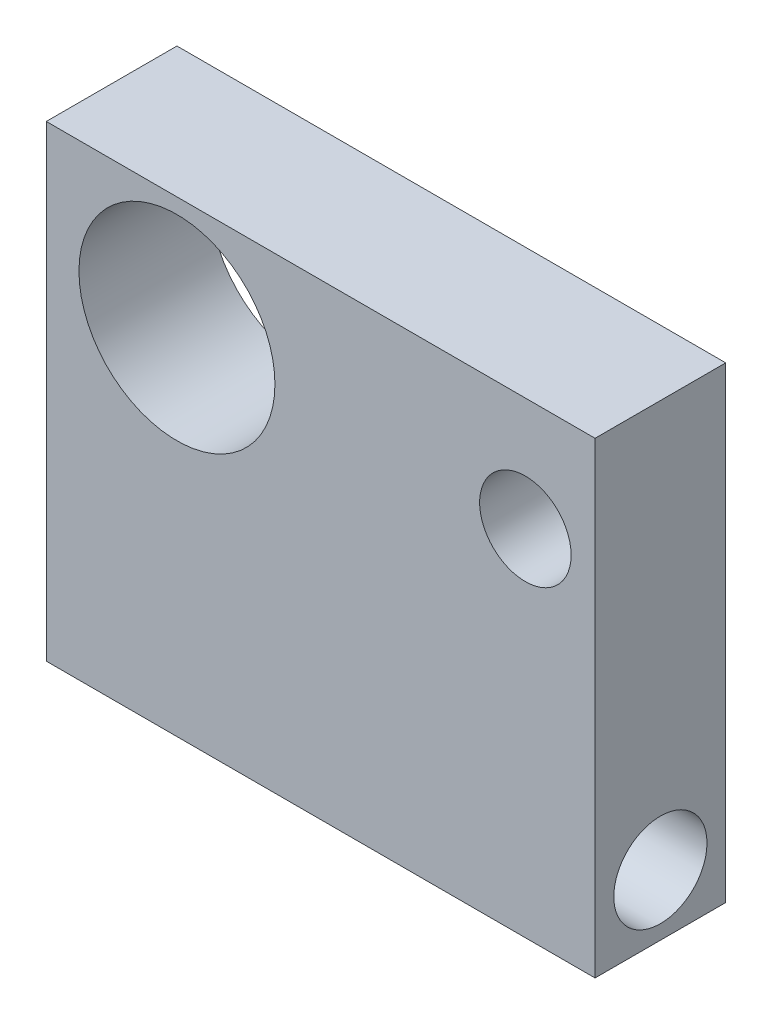
SolidWorks part; units mm, degrees
ref_plane "Front Plane" through (0, 0, 0) normal (0, 0, 1) x (1, 0, 0)
ref_plane "Top Plane" through (0, 0, 0) normal (0, 1, 0) x (1, 0, 0)
ref_plane "Right Plane" through (0, 0, 0) normal (1, 0, 0) x (0, 0, -1)
sketch "Sketch2" plane through (0, 0, 0) normal (0, 0, 1) x (1, 0, 0)
  line L1 (-31.9438, -27.208) -> (31.0562, -27.208)
  line L2 (-31.9438, -27.208) -> (-31.9438, 26.452)
  line L3 (-31.9438, 26.452) -> (31.0562, 26.452)
  line L4 (31.0562, -27.208) -> (31.0562, 26.452)
  line L5 (-31.9438, -27.208) -> (31.0562, 26.452) construction
  circle A0 centre (23.0562, 13.452) radius 5.25
  circle A1 centre (-16.9438, 13.452) radius 11.25
  point P0 (0, 0)
  dimension "D3" = 22.5
  dimension "D4" = 10.5
  dimension "D6" = 8
  dimension "D7" = 13
  dimension "D1" = 40.66
  dimension "D2" = 15
  dimension "D5" = 0
  dimension "D8" = 40
extrude "Boss-Extrude1" add sketch "Sketch2" along normal blind 15
sketch "Sketch3" plane through (31.0562, 0, 0) normal (1, 0, 0) x (0, 0, -1)
  line L0 (-15, -27.208) -> (0, -27.208) construction
  circle A0 centre (-7.5, -20.208) radius 5.35
  dimension "D1" = 10.7
  dimension "D2" = 7
extrude "Cut-Extrude1" cut sketch "Sketch3" against normal through all
